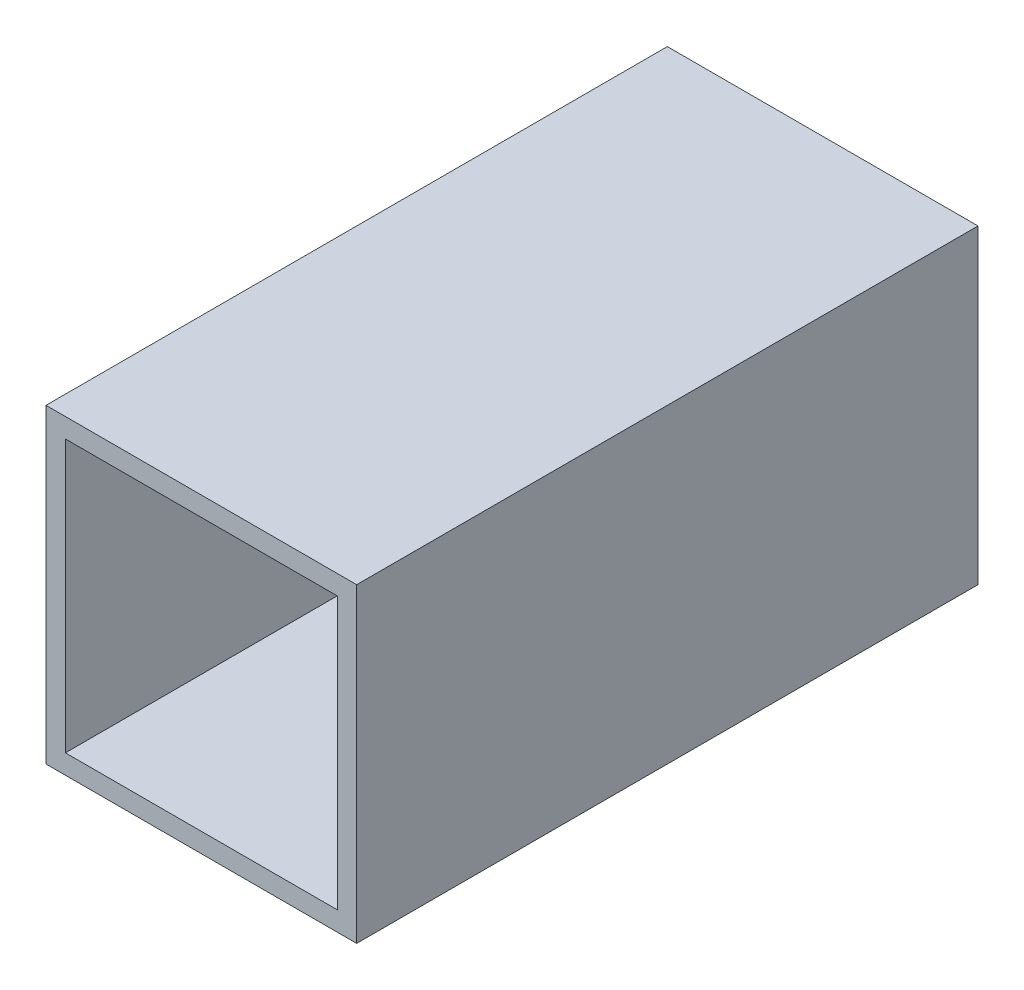
SolidWorks part; units mm, degrees
ref_plane "Front Plane" through (0, 0, 0) normal (0, 0, 1) x (1, 0, 0)
ref_plane "Top Plane" through (0, 0, 0) normal (0, 1, 0) x (1, 0, 0)
ref_plane "Right Plane" through (0, 0, 0) normal (1, 0, 0) x (0, 0, -1)
sketch "Sketch1" plane through (0, 0, 0) normal (0, 0, 1) x (1, 0, 0)
  line L1 (-11.1125, -11.1125) -> (11.1125, -11.1125)
  line L2 (-11.1125, -11.1125) -> (-11.1125, 11.1125)
  line L3 (-11.1125, 11.1125) -> (11.1125, 11.1125)
  line L4 (11.1125, -11.1125) -> (11.1125, 11.1125)
  line L5 (-11.1125, -11.1125) -> (11.1125, 11.1125) construction
  line L6 (-11.1125, 11.1125) -> (11.1125, -11.1125) construction
  line L7 (-12.7, -12.7) -> (12.7, -12.7)
  line L8 (-12.7, -12.7) -> (-12.7, 12.7)
  line L9 (-12.7, 12.7) -> (12.7, 12.7)
  line L10 (12.7, -12.7) -> (12.7, 12.7)
  line L11 (-12.7, -12.7) -> (12.7, 12.7) construction
  line L12 (-12.7, 12.7) -> (12.7, -12.7) construction
  point P0 (0, 0)
  point P6 (0, 0)
  dimension "D1" = 1.5875
  dimension "D2" = 25.4
extrude "Boss-Extrude1" add sketch "Sketch1" along normal blind 50.8
